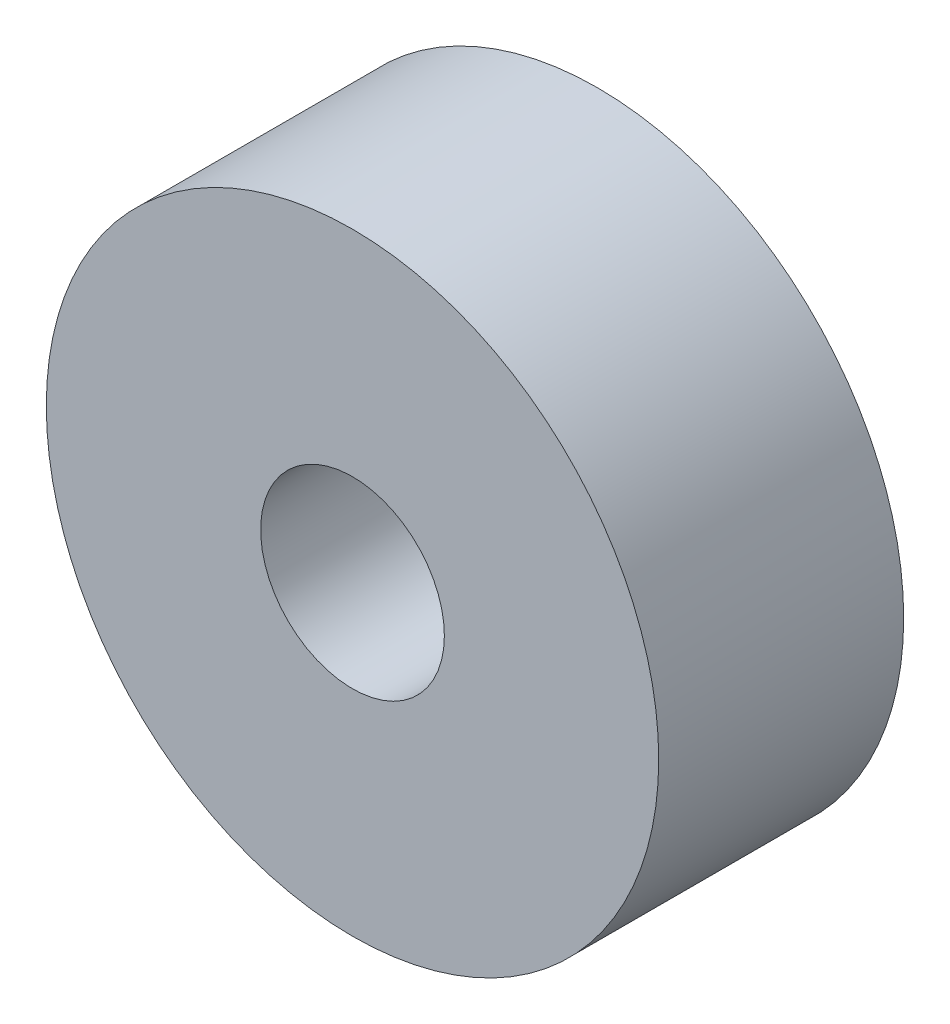
SolidWorks part; units mm, degrees
ref_plane "Спереди" through (0, 0, 0) normal (0, 0, 1) x (1, 0, 0)
ref_plane "Сверху" through (0, 0, 0) normal (0, 1, 0) x (1, 0, 0)
ref_plane "Справа" through (0, 0, 0) normal (1, 0, 0) x (0, 0, -1)
sketch "Эскиз1" plane through (0, 0, 0) normal (0, 0, 1) x (1, 0, 0)
  circle A0 centre (0, 0) radius 1.5
  circle A1 centre (0, 0) radius 5
  dimension "D1" = 10
  dimension "D2" = 3
extrude "Основа" add sketch "Эскиз1" along normal mid plane 4
